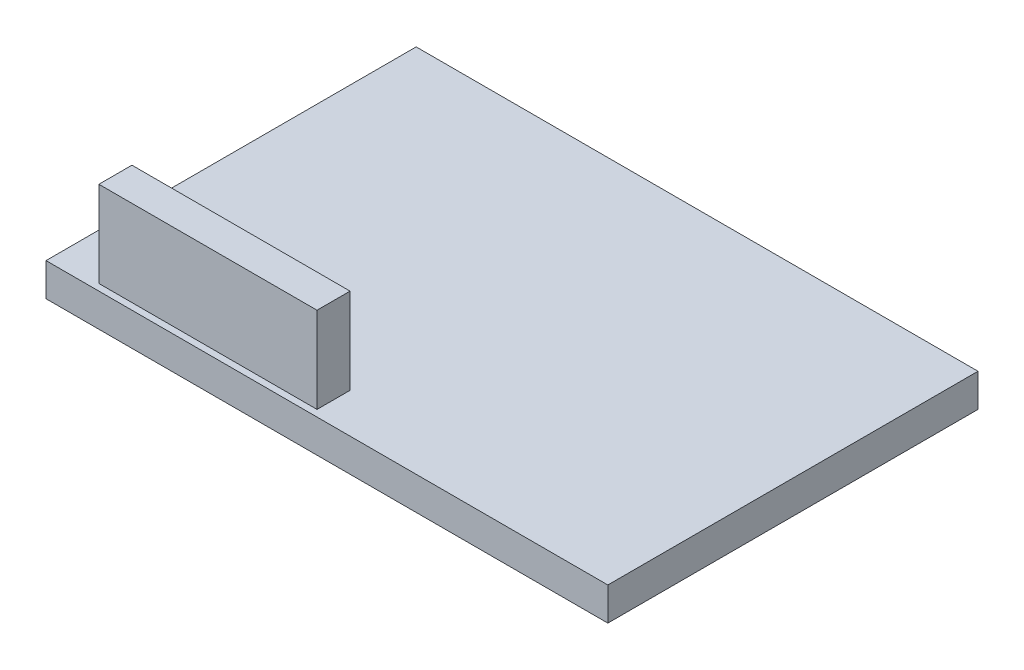
SolidWorks part; units mm, degrees
ref_plane "Спереди" through (0, 0, 0) normal (0, 0, 1) x (1, 0, 0)
ref_plane "Сверху" through (0, 0, 0) normal (0, 1, 0) x (1, 0, 0)
ref_plane "Справа" through (0, 0, 0) normal (1, 0, 0) x (0, 0, -1)
sketch "Эскиз1" plane through (0, 0, 0) normal (0, 1, 0) x (1, 0, 0)
  line L1 (0, 0) -> (85, 0)
  line L2 (0, 0) -> (0, 56)
  line L3 (0, 56) -> (85, 56)
  line L4 (85, 0) -> (85, 56)
extrude "Бобышка-Вытянуть1" add sketch "Эскиз1" along normal blind 5
sketch "Эскиз2" plane through (0, 5, 0) normal (0, 1, 0) x (1, 0, 0)
  line L0 (0, 56) -> (0, 0) construction
  line L1 (7, 1) -> (40, 1)
  line L2 (7, 1) -> (7, 6)
  line L3 (7, 6) -> (40, 6)
  line L4 (40, 1) -> (40, 6)
  line L5 (0, 0) -> (85, 0) construction
  dimension "D1" = 7
  dimension "D2" = 1
  dimension "D3" = 5
  dimension "D4" = 33
extrude "Бобышка-Вытянуть2" add sketch "Эскиз2" along normal blind 13
sketch "Эскиз3" plane through (0, 0, 0) normal (0, -1, 0) x (1, 0, 0)
  line L0 (85, -56) -> (0, -56) construction
  line L1 (76, -54) -> (7, -54)
  line L2 (76, -54) -> (76, -4)
  line L3 (76, -4) -> (7, -4)
  line L4 (7, -54) -> (7, -4)
  line L5 (85, 0) -> (85, -56) construction
  dimension "D1" = 50
  dimension "D2" = 69
  dimension "D3" = 2
  dimension "D4" = 9
extrude "Вырез-Вытянуть-Тонкостенный1" cut sketch "Эскиз3" against normal blind 1 thin thin type mid plane wall 1
